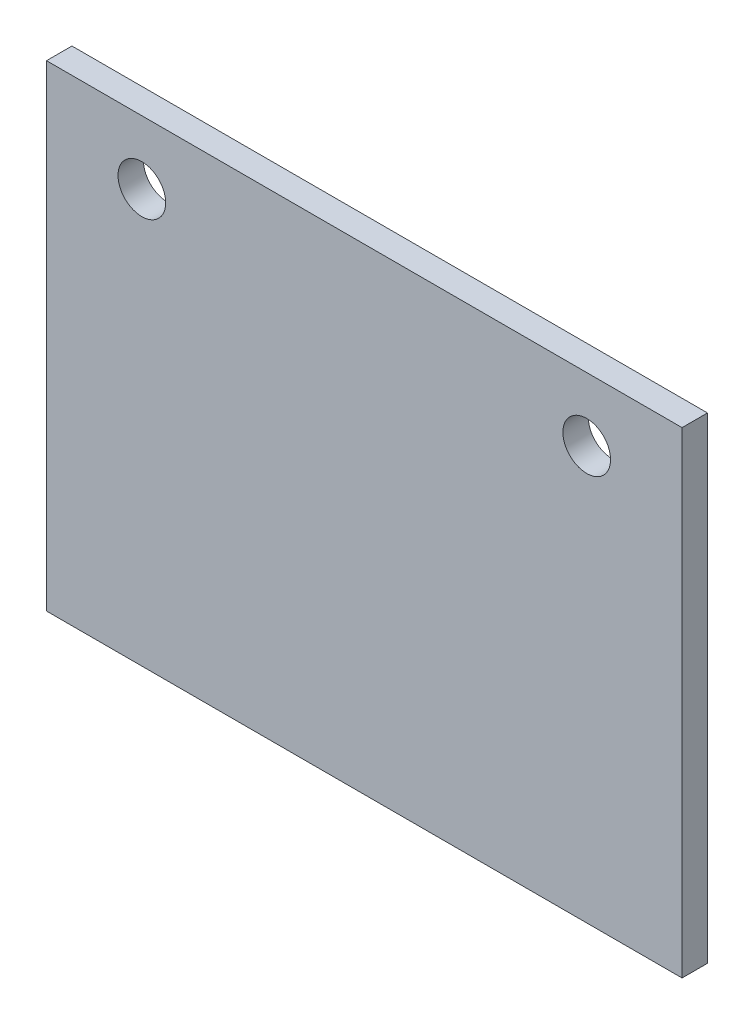
SolidWorks part; units mm, degrees
ref_plane "Спереди" through (0, 0, 0) normal (0, 0, 1) x (1, 0, 0)
ref_plane "Сверху" through (0, 0, 0) normal (0, 1, 0) x (1, 0, 0)
ref_plane "Справа" through (0, 0, 0) normal (1, 0, 0) x (0, 0, -1)
sketch "Эскиз1" plane through (0, 0, 0) normal (0, 0, 1) x (1, 0, 0)
  line L0 (0, 15) -> (0, -15) construction
  line L1 (20, -15) -> (-20, -15)
  line L2 (20, -15) -> (20, 15)
  line L3 (20, 15) -> (-20, 15)
  line L4 (-20, -15) -> (-20, 15)
  line L5 (20, -15) -> (-20, 15) construction
  line L6 (20, 15) -> (-20, -15) construction
  circle A0 centre (-14, 11) radius 1.5
  circle A1 centre (14, 11) radius 1.5
  point P0 (0, 0)
  dimension "D3" = 3
  dimension "D1" = 40
  dimension "D2" = 30
  dimension "D4" = 14
  dimension "D5" = 26
extrude "Бобышка-Вытянуть1" add sketch "Эскиз1" along normal blind 1.6
